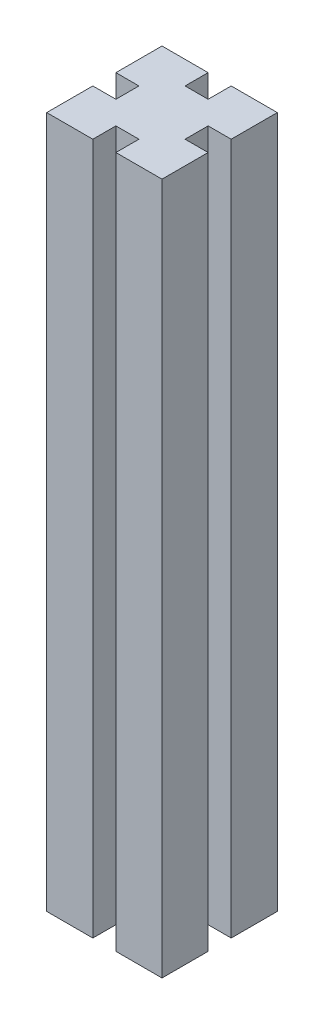
SolidWorks part; units mm, degrees
material "Kiefer"
ref_plane "Ebene vorne" through (0, 0, 0) normal (0, 0, 1) x (1, 0, 0)
ref_plane "Ebene oben" through (0, 0, 0) normal (0, 1, 0) x (1, 0, 0)
ref_plane "Ebene rechts" through (0, 0, 0) normal (1, 0, 0) x (0, 0, -1)
sketch "Skizze1" plane through (0, 0, 0) normal (0, 1, 0) x (1, 0, 0)
  line L1 (-12.5, 12.5) -> (12.5, 12.5)
  line L2 (-12.5, 12.5) -> (-12.5, -12.5)
  line L3 (-12.5, -12.5) -> (12.5, -12.5)
  line L4 (12.5, 12.5) -> (12.5, -12.5)
  line L5 (-12.5, 12.5) -> (12.5, -12.5) construction
  line L6 (-12.5, -12.5) -> (12.5, 12.5) construction
  point P0 (0, 0)
  dimension "D2" = 25
extrude "Aufsatz-Linear austragen1" add sketch "Skizze1" along normal blind 150
sketch "Skizze2" plane through (0, 150, 0) normal (0, 1, 0) x (1, 0, 0)
  line L0 (12.5, 12.5) -> (-12.5, 12.5) construction
  line L1 (-2.5, 17.5) -> (2.5, 17.5)
  line L2 (-2.5, 17.5) -> (-2.5, 7.5)
  line L3 (-2.5, 7.5) -> (2.5, 7.5)
  line L4 (2.5, 17.5) -> (2.5, 7.5)
  line L5 (-2.5, 17.5) -> (2.5, 7.5) construction
  line L6 (-2.5, 7.5) -> (2.5, 17.5) construction
  line L7 (17.5, 2.5) -> (17.5, -2.5)
  line L9 (17.5, 2.5) -> (7.5, 2.5)
  line L10 (7.5, 2.5) -> (7.5, -2.5)
  line L11 (17.5, -2.5) -> (7.5, -2.5)
  line L12 (17.5, 2.5) -> (7.5, -2.5) construction
  line L13 (7.5, 2.5) -> (17.5, -2.5) construction
  line L14 (2.5, -17.5) -> (-2.5, -17.5)
  line L15 (2.5, -17.5) -> (2.5, -7.5)
  line L16 (2.5, -7.5) -> (-2.5, -7.5)
  line L17 (-2.5, -17.5) -> (-2.5, -7.5)
  line L18 (2.5, -17.5) -> (-2.5, -7.5) construction
  line L19 (2.5, -7.5) -> (-2.5, -17.5) construction
  line L20 (-17.5, -2.5) -> (-17.5, 2.5)
  line L21 (-17.5, -2.5) -> (-7.5, -2.5)
  line L22 (-7.5, -2.5) -> (-7.5, 2.5)
  line L23 (-17.5, 2.5) -> (-7.5, 2.5)
  line L24 (-17.5, -2.5) -> (-7.5, 2.5) construction
  line L25 (-7.5, -2.5) -> (-17.5, 2.5) construction
  point P0 (0, 12.5)
  point P11 (12.5, 0)
  point P13 (0, 0)
  point P18 (0, -12.5)
  point P23 (-12.5, 0)
  point P28 (0, 0)
  dimension "D1" = 5
  dimension "D2" = 5
  dimension "D3" = 4
extrude "Schnitt-Linear austragen1" cut sketch "Skizze2" against normal blind 150
